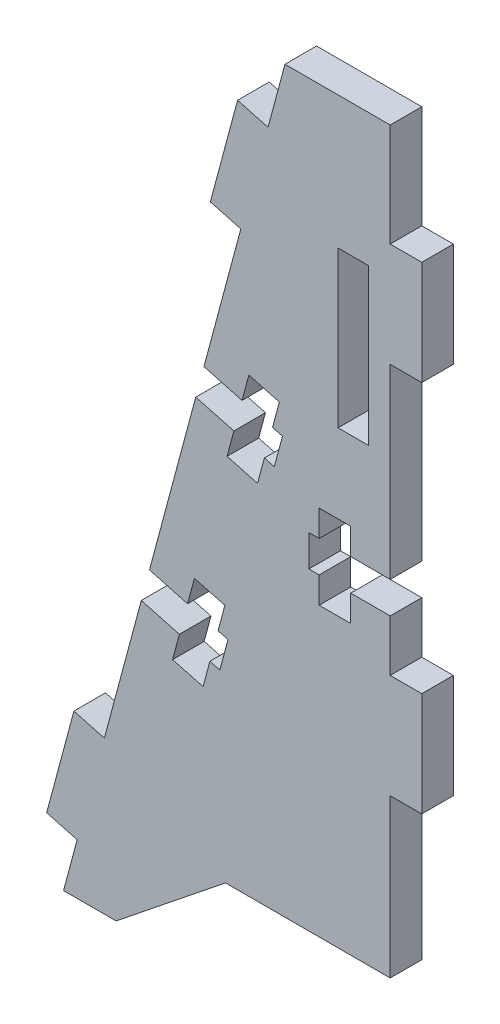
SolidWorks part; units mm, degrees
material "Balsa"
ref_plane "Alzado" through (0, 0, 0) normal (0, 0, 1) x (1, 0, 0)
ref_plane "Planta" through (0, 0, 0) normal (0, 1, 0) x (1, 0, 0)
ref_plane "Vista lateral" through (0, 0, 0) normal (1, 0, 0) x (0, 0, -1)
sketch "Croquis1" plane through (0, 0, 0) normal (0, 0, 1) x (1, 0, 0)
  line L0 (497.8557, 73.173) -> (497.8557, 63.273)
  line L1 (497.8557, 63.273) -> (494.8557, 63.273)
  line L2 (494.8557, 63.273) -> (494.8557, 45.5731)
  line L3 (494.8557, 42.5731) -> (494.8557, 41.0503)
  line L4 (494.8557, 40.6503) -> (494.8557, 37.6731)
  line L5 (494.8557, 37.6731) -> (497.8557, 37.6731)
  line L6 (497.8557, 37.6731) -> (497.8557, 27.7731)
  line L7 (497.8557, 73.173) -> (494.8557, 73.173)
  line L8 (484.8557, 82.973) -> (494.8557, 82.973)
  line L9 (494.8557, 82.973) -> (494.8557, 73.173)
  line L10 (497.8557, 27.7731) -> (494.8557, 27.7731)
  line L11 (480.6618, 67.3211) -> (477.764, 68.0975)
  line L12 (480.3522, 77.7568) -> (483.25, 76.9803)
  line L13 (465.1089, 9.2769) -> (462.2111, 10.0533)
  line L14 (464.7993, 19.7126) -> (467.6971, 18.9361)
  line L15 (483.25, 76.9803) -> (484.8557, 82.973)
  line L16 (480.6618, 67.3211) -> (477.1559, 54.2367)
  line L17 (476.3794, 51.339) -> (471.9795, 34.9182)
  line L18 (471.203, 32.0205) -> (467.6971, 18.9361)
  line L19 (494.8557, 27.7731) -> (494.8557, 12.7731)
  line L20 (494.8557, 12.7731) -> (479.2056, 12.7731)
  line L21 (465.1089, 9.2769) -> (463.8148, 4.4472)
  line L22 (463.8148, 4.4472) -> (468.8148, 4.4472)
  line L23 (468.8148, 4.4472) -> (479.2056, 12.7731)
  line L24 (494.8557, 40.6503) -> (494.8557, 41.0503)
  line L26 (480.7777, 53.2663) -> (477.1559, 54.2367)
  line L27 (484.323, 54.9049) -> (481.4249, 55.6815)
  line L28 (482.8994, 49.5919) -> (482.2523, 47.1771)
  line L29 (482.2523, 47.1771) -> (479.3542, 47.9537)
  line L30 (480.7777, 53.2663) -> (481.4249, 55.6815)
  line L31 (483.6759, 52.4897) -> (484.323, 54.9049)
  line L32 (484.6176, 52.2374) -> (483.6759, 52.4897)
  line L33 (480.0013, 50.3685) -> (479.3542, 47.9537)
  line L34 (483.8412, 49.3396) -> (482.8994, 49.5919)
  line L35 (476.3794, 51.339) -> (480.0013, 50.3685)
  line L36 (484.6176, 52.2374) -> (483.8412, 49.3396)
  line L37 (475.6014, 33.9477) -> (471.9795, 34.9182)
  line L38 (479.1466, 35.5864) -> (476.2485, 36.363)
  line L39 (477.723, 30.2734) -> (477.076, 27.8586)
  line L40 (477.076, 27.8586) -> (474.1779, 28.6352)
  line L41 (475.6014, 33.9477) -> (476.2485, 36.363)
  line L42 (478.4995, 33.1712) -> (479.1466, 35.5864)
  line L43 (479.4413, 32.9189) -> (478.4995, 33.1712)
  line L44 (474.8249, 31.05) -> (474.1779, 28.6352)
  line L45 (478.6648, 30.0211) -> (477.723, 30.2734)
  line L46 (471.203, 32.0205) -> (474.8249, 31.05)
  line L47 (479.4413, 32.9189) -> (478.6648, 30.0211)
  line L48 (491.1061, 45.5731) -> (494.8557, 45.5731)
  line L49 (488.1057, 48.0735) -> (491.1061, 48.0735)
  line L50 (488.1057, 42.5731) -> (488.1057, 40.0731)
  line L51 (488.1057, 40.0731) -> (491.1061, 40.0731)
  line L52 (491.1061, 45.5731) -> (491.1061, 48.0735)
  line L53 (488.1057, 45.5731) -> (488.1057, 48.0735)
  line L54 (487.1307, 45.5731) -> (488.1057, 45.5731)
  line L55 (491.1061, 42.5731) -> (491.1061, 40.0731)
  line L56 (487.1307, 42.5731) -> (488.1057, 42.5731)
  line L57 (494.8557, 42.5731) -> (491.1061, 42.5731)
  line L58 (487.1307, 45.5731) -> (487.1307, 42.5731)
  line L116 (480.3522, 77.7568) -> (477.764, 68.0975)
  line L117 (464.7993, 19.7126) -> (462.2111, 10.0533)
  dimension "D1" = 70.1999
extrude "Saliente-Extruir1" add sketch "Croquis1" along normal mid plane 3
sketch "Croquis2" plane through (0, 0, 1.5) normal (0, 0, 1) x (1, 0, 0)
  line L0 (491.3557, 55.573) -> (491.3557, 70.373) construction
  line L1 (489.9057, 55.573) -> (492.8057, 55.573)
  line L2 (489.9057, 55.573) -> (489.9057, 70.373)
  line L3 (489.9057, 70.373) -> (492.8057, 70.373)
  line L4 (492.8057, 55.573) -> (492.8057, 70.373)
  line L5 (492.8057, 62.973) -> (489.9057, 62.973) construction
  line L6 (494.8557, 82.973) -> (484.8557, 82.973) construction
  line L7 (497.8557, 63.273) -> (497.8557, 73.173) construction
  dimension "D1" = 20
  dimension "D2" = 6.5
  dimension "D3" = 2.9
  dimension "D4" = 14.8
extrude "Cortar-Extruir1" cut sketch "Croquis2" against normal blind 10
